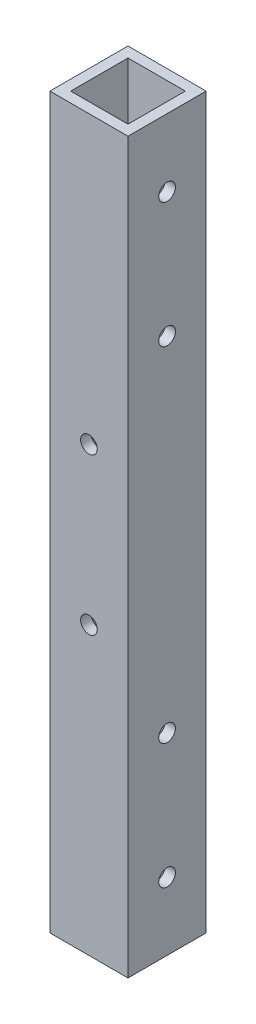
SolidWorks part; units mm, degrees
ref_plane "Front Plane" through (0, 0, 0) normal (0, 0, 1) x (1, 0, 0)
ref_plane "Top Plane" through (0, 0, 0) normal (0, 1, 0) x (1, 0, 0)
ref_plane "Right Plane" through (0, 0, 0) normal (1, 0, 0) x (0, 0, -1)
sketch "Sketch1" plane through (0, 0, 0) normal (0, 1, 0) x (1, 0, 0)
  line L0 (13, 2) -> (13, 13)
  line L1 (0, 0) -> (15, 0)
  line L2 (0, 0) -> (0, 15)
  line L3 (0, 15) -> (15, 15)
  line L4 (15, 0) -> (15, 15)
  line L5 (2, 13) -> (13, 13)
  line L6 (2, 2) -> (2, 13)
  line L7 (2, 2) -> (13, 2)
  dimension "D1" = 15
  dimension "D2" = 2
extrude "Boss-Extrude1" add sketch "Sketch1" along normal blind 140
sketch "Sketch2" plane through (15, 0, 0) normal (1, 0, 0) x (0, 0, -1)
  line L0 (0, 70) -> (15, 70) construction
  line L1 (0, 140) -> (0, 0) construction
  line L2 (15, 140) -> (15, 0) construction
  circle A0 centre (7.5, 13) radius 1.6
  circle A1 centre (7.5, 37) radius 1.6
  circle A2 centre (7.5, 103) radius 1.6
  circle A3 centre (7.5, 127) radius 1.6
  dimension "D1" = 3.2
extrude "Cut-Extrude1" cut sketch "Sketch2" against normal through all
sketch "Sketch3" plane through (0, 0, 0) normal (0, 0, 1) x (1, 0, 0)
  line L0 (15, 70) -> (0, 70) construction
  line L1 (15, 140) -> (15, 0) construction
  line L2 (0, 140) -> (0, 0) construction
  line L3 (7.5, 140) -> (7.5, 0) construction
  line L4 (0, 140) -> (15, 140) construction
  line L5 (0, 0) -> (15, 0) construction
  circle A0 centre (7.5, 85) radius 1.6
  circle A1 centre (7.5, 55) radius 1.6
  dimension "D1" = 15
  dimension "D3" = 3.2
  dimension "D2" = 15
extrude "Cut-Extrude2" cut sketch "Sketch3" against normal through all
